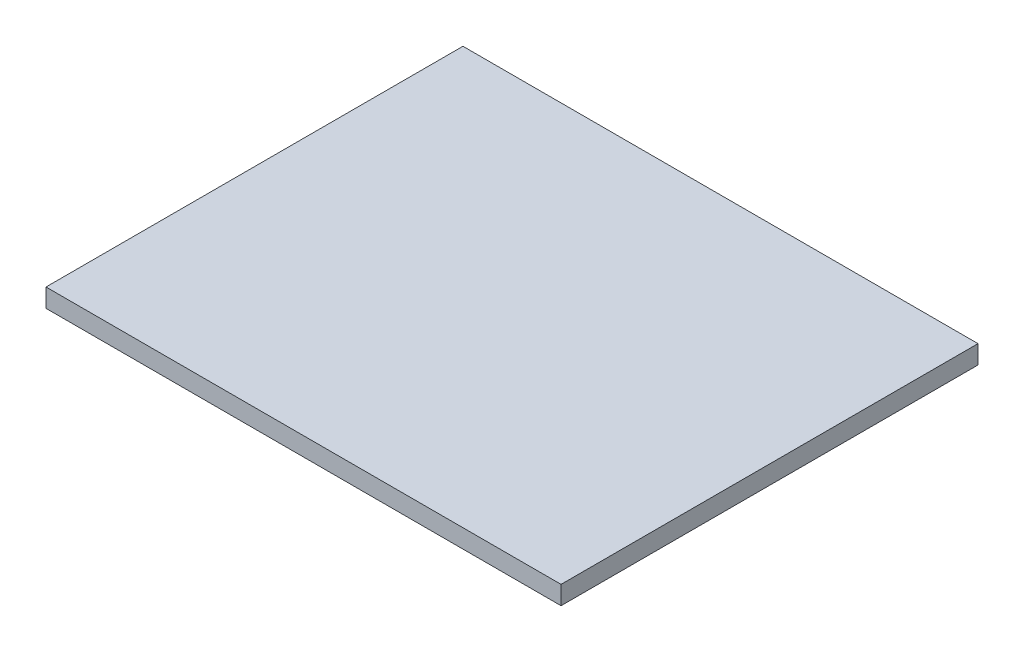
SolidWorks part; units mm, degrees
ref_plane "Front Plane" through (0, 0, 0) normal (0, 0, 1) x (1, 0, 0)
ref_plane "Top Plane" through (0, 0, 0) normal (0, 1, 0) x (1, 0, 0)
ref_plane "Right Plane" through (0, 0, 0) normal (1, 0, 0) x (0, 0, -1)
sketch "Sketch1" plane through (0, 0, 0) normal (0, 1, 0) x (1, 0, 0)
  line L1 (-45.7927, 36.9171) -> (154.7657, 36.9171)
  line L2 (-45.7927, 36.9171) -> (-45.7927, -125.4397)
  line L3 (-45.7927, -125.4397) -> (154.7657, -125.4397)
  line L4 (154.7657, 36.9171) -> (154.7657, -125.4397)
  dimension "D1" = 200.5584
  dimension "D2" = 162.3568
extrude "Boss-Extrude1" add sketch "Sketch1" along normal blind 7.2136
equation "\"D2@Sketch1\"=\"Base Width@Assembled Container.Assembly\""
equation "\"D1@Sketch1\"=\"Base Length@Assembled Container.Assembly\""
equation "\"D1@Boss-Extrude1\"=\"Acrylic Thickness@Assembled Container.Assembly\""
